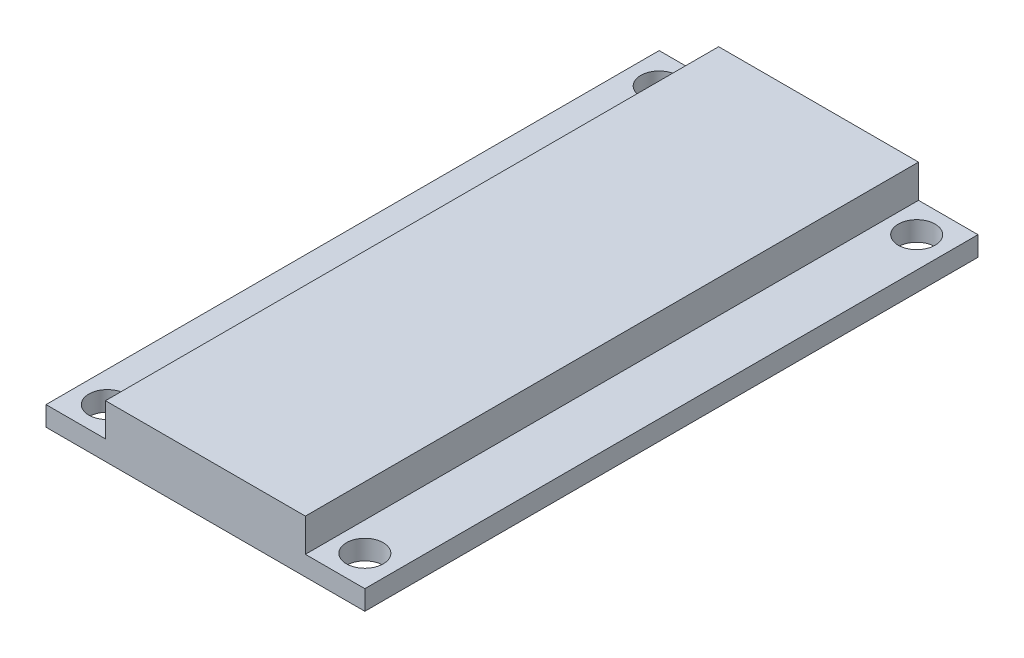
SolidWorks part; units mm, degrees
ref_plane "Front Plane" through (0, 0, 0) normal (0, 0, 1) x (1, 0, 0)
ref_plane "Top Plane" through (0, 0, 0) normal (0, 1, 0) x (1, 0, 0)
ref_plane "Right Plane" through (0, 0, 0) normal (1, 0, 0) x (0, 0, -1)
sketch "Sketch1" plane through (0, 0, 0) normal (0, 1, 0) x (1, 0, 0)
  line L1 (0, 0) -> (26, 0)
  line L2 (0, 0) -> (0, 50)
  line L3 (0, 50) -> (26, 50)
  line L4 (26, 0) -> (26, 50)
  dimension "D1" = 26
  dimension "D2" = 50
extrude "Boss-Extrude1" add sketch "Sketch1" along normal blind 1.6
sketch "Sketch2" plane through (0, 1.6, 0) normal (0, 1, 0) x (1, 0, 0)
  line L0 (0, 2.5) -> (2.5, 2.5) construction
  line L1 (0, 50) -> (0, 0) construction
  line L2 (2.5, 2.5) -> (2.5, 0) construction
  line L3 (0, 0) -> (26, 0) construction
  line L4 (2.5, 1) -> (2.5, 0) construction
  line L5 (13, 0) -> (13, 9.1277) construction
  line L6 (0, 25) -> (8.2284, 25) construction
  circle A0 centre (2.5, 2.5) radius 1.5
  circle A1 centre (23.5, 2.5) radius 1.5
  circle A2 centre (23.5, 47.5) radius 1.5
  circle A3 centre (2.5, 47.5) radius 1.5
  dimension "D2" = 3
  dimension "D1" = 1
extrude "Cut-Extrude1" cut sketch "Sketch2" against normal through all
sketch "Sketch3" plane through (0, 1.6, 0) normal (0, 1, 0) x (1, 0, 0)
  line L0 (13, 50) -> (13, 0) construction
  line L1 (26, 50) -> (0, 50) construction
  line L2 (0, 0) -> (26, 0) construction
  line L4 (21.15, 50) -> (4.85, 50)
  line L5 (21.15, 50) -> (21.15, 0)
  line L6 (21.15, 0) -> (4.85, 0)
  line L7 (4.85, 50) -> (4.85, 0)
  line L8 (21.15, 50) -> (4.85, 0) construction
  line L9 (21.15, 0) -> (4.85, 50) construction
  point P6 (13, 25)
  dimension "D1" = 16.3
extrude "Boss-Extrude2" add sketch "Sketch3" along normal blind 2.7
